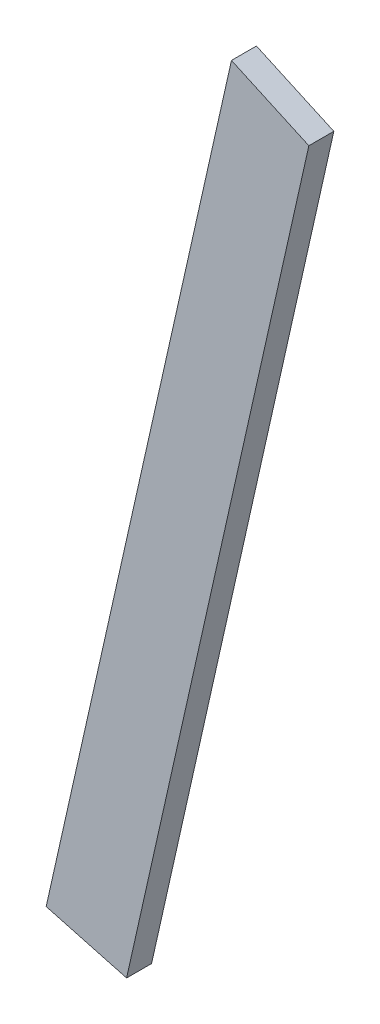
SolidWorks part; units mm, degrees
ref_plane "Front Plane" through (0, 0, 0) normal (0, 0, 1) x (1, 0, 0)
ref_plane "Top Plane" through (0, 0, 0) normal (0, 1, 0) x (1, 0, 0)
ref_plane "Right Plane" through (0, 0, 0) normal (1, 0, 0) x (0, 0, -1)
sketch "Sketch6" plane through (0, 0, 0) normal (0, 0, 1) x (1, 0, 0)
  line L0 (-596.8655, 1608.234) -> (-738.2517, 978.4228)
  line L1 (-738.2517, 978.4228) -> (-676.8862, 961.8748)
  line L2 (-537.8111, 1581.3911) -> (-676.8862, 961.8748)
  line L3 (-596.8655, 1608.234) -> (-537.8111, 1581.3911)
extrude "Boss-Extrude1" add sketch "Sketch6" along normal blind 19.05
